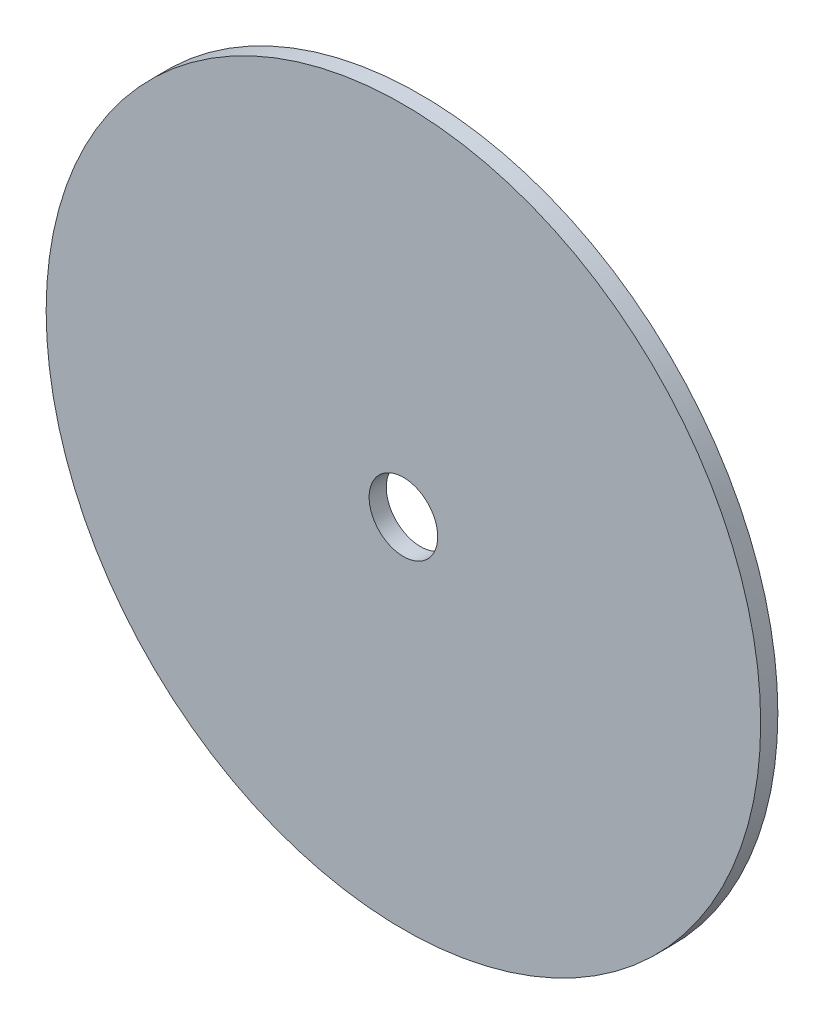
SolidWorks part; units mm, degrees
material "ABS"
ref_plane "Front Plane" through (0, 0, 0) normal (0, 0, 1) x (1, 0, 0)
ref_plane "Top Plane" through (0, 0, 0) normal (0, 1, 0) x (1, 0, 0)
ref_plane "Right Plane" through (0, 0, 0) normal (1, 0, 0) x (0, 0, -1)
sketch "Sketch1" plane through (0, 0, 0) normal (0, 0, 1) x (1, 0, 0)
  circle A0 centre (0, 0) radius 62.5
  circle A1 centre (0, 0) radius 6
  dimension "D1" = 125
  dimension "D2" = 12
extrude "Boss-Extrude1" add sketch "Sketch1" along normal blind 3
